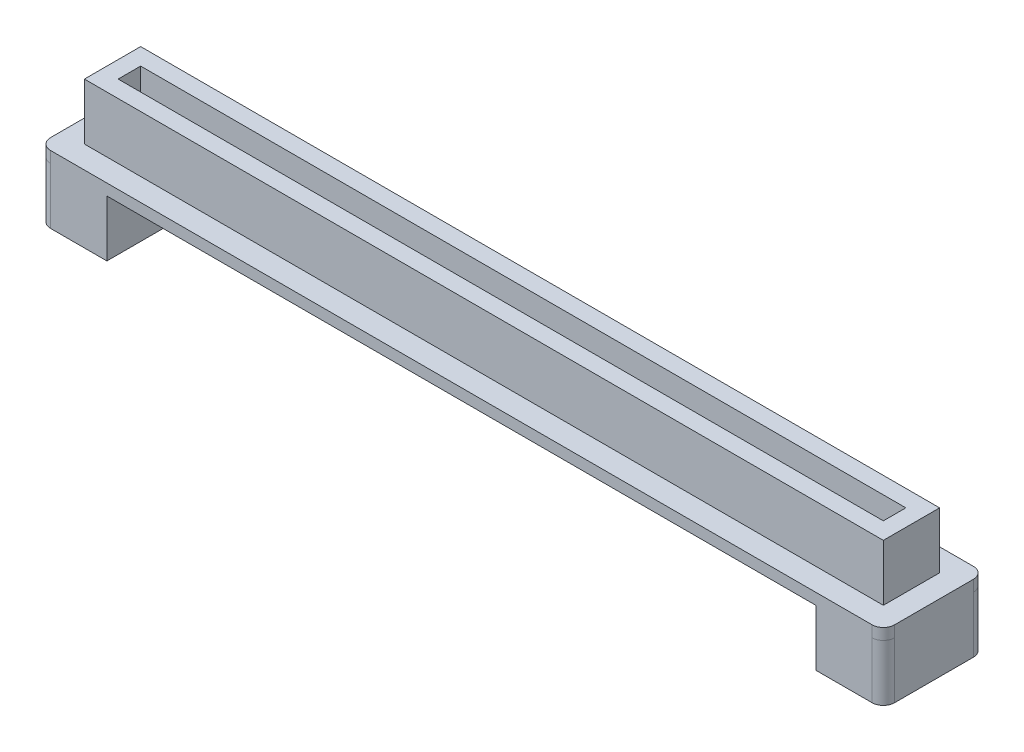
SolidWorks part; units mm, degrees
ref_plane "Front Plane" through (0, 0, 0) normal (0, 0, 1) x (1, 0, 0)
ref_plane "Top Plane" through (0, 0, 0) normal (0, 1, 0) x (1, 0, 0)
ref_plane "Right Plane" through (0, 0, 0) normal (1, 0, 0) x (0, 0, -1)
sketch "Sketch1" plane through (0, 0, 0) normal (0, 1, 0) x (1, 0, 0)
  line L1 (0, 0) -> (75, 0)
  line L2 (0, 0) -> (0, 9)
  line L3 (0, 9) -> (75, 9)
  line L4 (75, 0) -> (75, 9)
  dimension "D1" = 9
  dimension "D2" = 75
extrude "Boss-Extrude1" add sketch "Sketch1" along normal blind 1
fillet "Fillet1" radius 1 4 edges at (75, 0.5, -9) (75, 0.5, 0) (0, 0.5, 0) (0, 0.5, -9)
sketch "Sketch8" plane through (0, 0, 0) normal (0, 1, 0) x (1, 0, 0)
  line L1 (2, 7) -> (73, 7)
  line L2 (2, 7) -> (2, 2)
  line L3 (2, 2) -> (73, 2)
  line L4 (73, 7) -> (73, 2)
  line L7 (74, 9) -> (1, 9) construction
  line L9 (0, 8) -> (0, 1) construction
  dimension "D1" = 5
  dimension "D2" = 2
  dimension "D3" = 71
  dimension "D4" = 2
extrude "Boss-Extrude2" add sketch "Sketch8" along normal blind 6
shell "Shell1" thickness 1.5
sketch "Sketch9" plane through (0, 0, 0) normal (0, -1, 0) x (-1, 0, 0)
  line L1 (0, 9) -> (-6, 9)
  line L2 (0, 9) -> (0, 0)
  line L3 (0, 0) -> (-6, 0)
  line L4 (-6, 9) -> (-6, 0)
  line L5 (-1, 0) -> (-74, 0) construction
  line L6 (0, 8) -> (0, 1) construction
  dimension "D1" = 6
  dimension "D3" = 9
extrude "Boss-Extrude3" add sketch "Sketch9" along normal blind 5
pattern_linear "LPattern1" count 2 spacing 69 along (1, 0, 0) of "Boss-Extrude3"
fillet "Fillet2" radius 1 12 edges at (0, 0, -0.5) (0, 0, -8.5) (0, -2.5, 0) (0.5, 0, -9) (0, -2.5, -9) (0.5, 0, 0) (74.5, 0, -9) (75, 0, -8.5) (75, 0, -0.5) (75, -2.5, -9) (74.5, 0, 0) (75, -2.5, 0)
